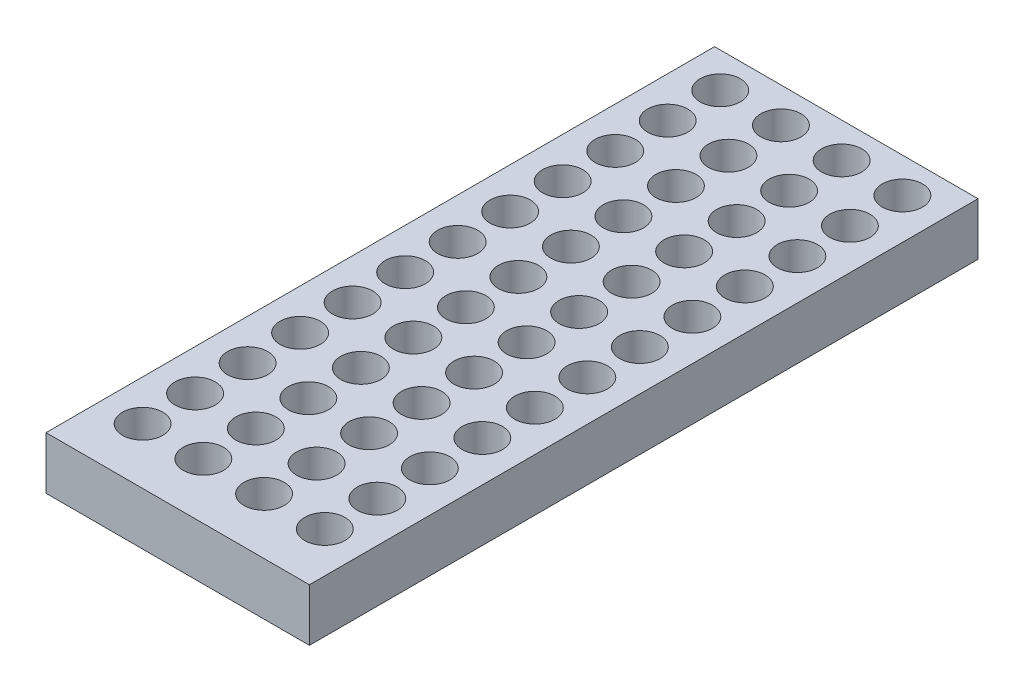
SolidWorks part; units mm, degrees
ref_plane "Front Plane" through (0, 0, 0) normal (0, 0, 1) x (1, 0, 0)
ref_plane "Top Plane" through (0, 0, 0) normal (0, 1, 0) x (1, 0, 0)
ref_plane "Right Plane" through (0, 0, 0) normal (1, 0, 0) x (0, 0, -1)
sketch "Sketch1" plane through (0, 0, 0) normal (0, 1, 0) x (1, 0, 0)
  line L0 (-26.025, 70.5) -> (-37.625, 70.5) construction
  line L1 (37.625, -95.5) -> (-37.625, -95.5)
  line L2 (37.625, -95.5) -> (37.625, 95.5)
  line L3 (37.625, 95.5) -> (-37.625, 95.5)
  line L4 (-37.625, -95.5) -> (-37.625, 95.5)
  line L5 (37.625, -95.5) -> (-37.625, 95.5) construction
  line L6 (37.625, 95.5) -> (-37.625, -95.5) construction
  line L7 (-26.025, 85.5) -> (-37.625, 85.5) construction
  line L8 (-26.025, 85.5) -> (-26.025, 95.5) construction
  line L9 (26.025, 85.5) -> (37.625, 85.5) construction
  line L10 (-14.425, 85.5) -> (-26.025, 85.5) construction
  circle A0 centre (-26.025, 85.5) radius 5.75
  circle A1 centre (-8.675, 85.5) radius 5.75
  circle A2 centre (8.675, 85.5) radius 5.75
  circle A3 centre (26.025, 85.5) radius 5.75
  circle A6 centre (-26.025, 70.5) radius 5.75
  circle A7 centre (-8.675, 70.5) radius 5.75
  circle A8 centre (8.675, 70.5) radius 5.75
  circle A9 centre (26.025, 70.5) radius 5.75
  circle A12 centre (-26.025, 55.5) radius 5.75
  circle A13 centre (-8.675, 55.5) radius 5.75
  circle A14 centre (8.675, 55.5) radius 5.75
  circle A15 centre (26.025, 55.5) radius 5.75
  circle A18 centre (-26.025, 40.5) radius 5.75
  circle A19 centre (-8.675, 40.5) radius 5.75
  circle A20 centre (8.675, 40.5) radius 5.75
  circle A21 centre (26.025, 40.5) radius 5.75
  circle A24 centre (-26.025, 25.5) radius 5.75
  circle A25 centre (-8.675, 25.5) radius 5.75
  circle A26 centre (8.675, 25.5) radius 5.75
  circle A27 centre (26.025, 25.5) radius 5.75
  circle A30 centre (-26.025, 10.5) radius 5.75
  circle A31 centre (-8.675, 10.5) radius 5.75
  circle A32 centre (8.675, 10.5) radius 5.75
  circle A33 centre (26.025, 10.5) radius 5.75
  circle A36 centre (-26.025, -4.5) radius 5.75
  circle A37 centre (-8.675, -4.5) radius 5.75
  circle A38 centre (8.675, -4.5) radius 5.75
  circle A39 centre (26.025, -4.5) radius 5.75
  circle A42 centre (-26.025, -19.5) radius 5.75
  circle A43 centre (-8.675, -19.5) radius 5.75
  circle A44 centre (8.675, -19.5) radius 5.75
  circle A45 centre (26.025, -19.5) radius 5.75
  circle A48 centre (-26.025, -34.5) radius 5.75
  circle A49 centre (-8.675, -34.5) radius 5.75
  circle A50 centre (8.675, -34.5) radius 5.75
  circle A51 centre (26.025, -34.5) radius 5.75
  circle A54 centre (-26.025, -49.5) radius 5.75
  circle A55 centre (-8.675, -49.5) radius 5.75
  circle A56 centre (8.675, -49.5) radius 5.75
  circle A57 centre (26.025, -49.5) radius 5.75
  circle A58 centre (-26.025, -64.5) radius 5.75
  circle A59 centre (-8.675, -64.5) radius 5.75
  circle A60 centre (8.675, -64.5) radius 5.75
  circle A61 centre (26.025, -64.5) radius 5.75
  circle A62 centre (-26.025, -79.5) radius 5.75
  circle A63 centre (-8.675, -79.5) radius 5.75
  circle A64 centre (8.675, -79.5) radius 5.75
  circle A65 centre (26.025, -79.5) radius 5.75
  point P0 (0, 0)
  dimension "D1" = 11.5
  dimension "D3" = 15
  dimension "D5" = 10
  dimension "D7" = 191
  dimension "D9" = 75.25
  dimension "D2" = 4
  dimension "D6" = 12
extrude "Boss-Extrude1" add sketch "Sketch1" along normal blind 15
sketch "Sketch2" plane through (0, 0, 0) normal (0, -1, 0) x (1, 0, 0)
  line L1 (37.625, -95.5) -> (-37.625, -95.5)
  line L2 (37.625, -95.5) -> (37.625, 95.5)
  line L3 (37.625, 95.5) -> (-37.625, 95.5)
  line L4 (-37.625, -95.5) -> (-37.625, 95.5)
  line L5 (37.625, -95.5) -> (-37.625, 95.5) construction
  line L6 (37.625, 95.5) -> (-37.625, -95.5) construction
  point P0 (0, 0)
